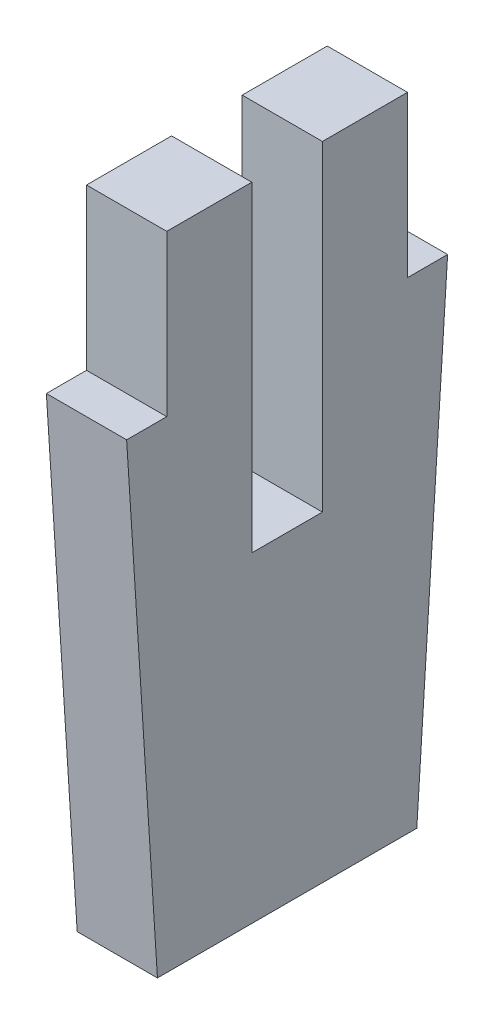
SolidWorks part; units mm, degrees
ref_plane "Front Plane" through (0, 0, 0) normal (0, 0, 1) x (1, 0, 0)
ref_plane "Top Plane" through (0, 0, 0) normal (0, 1, 0) x (1, 0, 0)
ref_plane "Right Plane" through (0, 0, 0) normal (1, 0, 0) x (0, 0, -1)
sketch "Sketch1" plane through (0, 0, 0) normal (1, 0, 0) x (0, 0, -1)
  line L0 (0, 55) -> (0, -55) construction
  line L1 (0, 50.8) -> (6.731, 50.8)
  line L2 (0, 50.8) -> (0, 38.1)
  line L3 (-3.175, 38.1) -> (22.225, 38.1) construction
  line L4 (19.05, 50.8) -> (19.05, 38.1)
  line L5 (0, 38.1) -> (-3.175, 38.1)
  line L6 (9.525, 38.1) -> (9.525, 6.35) construction
  line L7 (19.05, 38.1) -> (22.225, 38.1)
  line L8 (-1.143, 6.35) -> (20.193, 6.35) construction
  line L9 (-3.175, 38.1) -> (-1.143, 6.35)
  line L10 (22.225, 38.1) -> (20.193, 6.35)
  line L11 (20.193, 6.35) -> (19.7866, 0)
  line L12 (-1.143, 6.35) -> (-0.7366, 0)
  line L13 (-0.7366, 0) -> (19.7866, 0)
  line L14 (55, 0) -> (-55, 0) construction
  line L15 (12.319, 50.8) -> (19.05, 50.8)
  line L16 (0, 50.8) -> (12.319, 50.8) construction
  line L17 (12.319, 50.8) -> (12.319, 25.4)
  line L18 (12.319, 25.4) -> (6.731, 25.4)
  line L19 (6.731, 50.8) -> (6.731, 25.4)
  line L20 (12.319, 50.8) -> (6.731, 25.4) construction
  line L21 (12.319, 25.4) -> (6.731, 50.8) construction
  line L27 (12.319, 50.8) -> (19.05, 50.8) construction
  point P8 (9.525, 38.1)
  dimension "D1" = 12.7
  dimension "D2" = 19.05
  dimension "D3" = 25.4
  dimension "D4" = 31.75
  dimension "D5" = 21.336
  dimension "D6" = 6.35
  dimension "D7" = 20.5232
  dimension "D8" = 20.5232
  dimension "D9" = 5.588
  dimension "D10" = 25.4
  dimension "D11" = 50.8
extrude "Boss-Extrude1" add sketch "Sketch1" along normal blind 6.35
